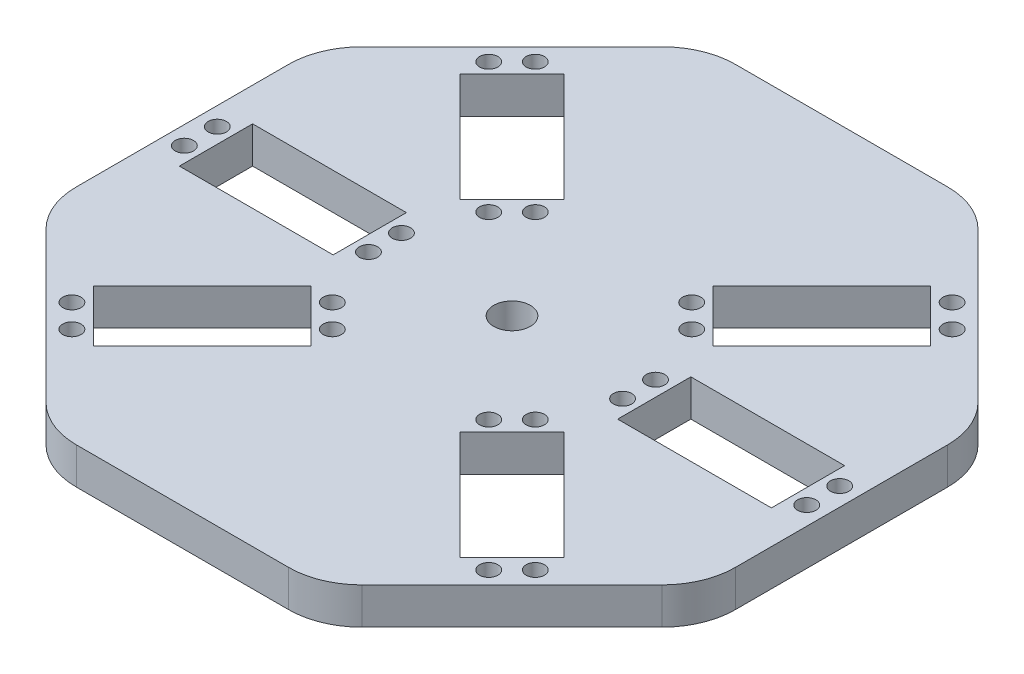
SolidWorks part; units mm, degrees
ref_plane "Front Plane" through (0, 0, 0) normal (0, 0, 1) x (1, 0, 0)
ref_plane "Top Plane" through (0, 0, 0) normal (0, 1, 0) x (1, 0, 0)
ref_plane "Right Plane" through (0, 0, 0) normal (1, 0, 0) x (0, 0, -1)
sketch "Sketch1" plane through (0, 0, 0) normal (0, 1, 0) x (1, 0, 0)
  line L0 (21.3546, -27.7186) -> (56.9221, -63.2861)
  line L1 (-90, -37.2792) -> (-37.2792, -90)
  line L2 (-37.2792, -90) -> (37.2792, -90)
  line L3 (37.2792, -90) -> (90, -37.2792)
  line L4 (90, -37.2792) -> (90, 37.2792)
  line L5 (90, 37.2792) -> (37.2792, 90)
  line L6 (37.2792, 90) -> (-37.2792, 90)
  line L7 (-37.2792, 90) -> (-90, 37.2792)
  line L8 (-90, 37.2792) -> (-90, -37.2792)
  line L9 (21.3546, -27.7186) -> (27.7186, -21.3546)
  line L10 (56.9221, -63.2861) -> (63.2861, -56.9221)
  line L11 (27.7186, -21.3546) -> (63.2861, -56.9221)
  line L12 (63.6396, -63.6396) -> (0, 0) construction
  line L13 (34.5422, -20.4) -> (20.4, -34.5422)
  line L14 (34.5422, -20.4) -> (64.2407, -50.0985)
  line L15 (20.4, -34.5422) -> (50.0985, -64.2407)
  line L16 (64.2407, -50.0985) -> (50.0985, -64.2407)
  line L17 (10, -38.85) -> (-10, -38.85) [skipped]
  line L18 (10, -38.85) -> (10, -80.85) [skipped]
  line L19 (10, -80.85) -> (-10, -80.85) [skipped]
  line L20 (-10, -38.85) -> (-10, -80.85) [skipped]
  line L21 (-20.4, -34.5422) -> (-34.5422, -20.4)
  line L22 (-20.4, -34.5422) -> (-50.0985, -64.2407)
  line L23 (-50.0985, -64.2407) -> (-64.2407, -50.0985)
  line L24 (-34.5422, -20.4) -> (-64.2407, -50.0985)
  line L25 (-38.85, -10) -> (-38.85, 10)
  line L26 (-38.85, -10) -> (-80.85, -10)
  line L27 (-80.85, -10) -> (-80.85, 10)
  line L28 (-38.85, 10) -> (-80.85, 10)
  line L29 (-34.5422, 20.4) -> (-20.4, 34.5422)
  line L30 (-34.5422, 20.4) -> (-64.2407, 50.0985)
  line L31 (-64.2407, 50.0985) -> (-50.0985, 64.2407)
  line L32 (-20.4, 34.5422) -> (-50.0985, 64.2407)
  line L33 (-10, 38.85) -> (10, 38.85) [skipped]
  line L34 (-10, 38.85) -> (-10, 80.85) [skipped]
  line L35 (-10, 80.85) -> (10, 80.85) [skipped]
  line L36 (10, 38.85) -> (10, 80.85) [skipped]
  line L37 (20.4, 34.5422) -> (34.5422, 20.4)
  line L38 (20.4, 34.5422) -> (50.0985, 64.2407)
  line L39 (50.0985, 64.2407) -> (64.2407, 50.0985)
  line L40 (34.5422, 20.4) -> (64.2407, 50.0985)
  line L41 (38.85, 10) -> (38.85, -10)
  line L42 (38.85, 10) -> (80.85, 10)
  line L43 (80.85, 10) -> (80.85, -10)
  line L44 (38.85, -10) -> (80.85, -10)
  circle A0 centre (0, 0) radius 90 construction
  circle A5 centre (56.9221, -63.2861) radius 2.5
  circle A6 centre (63.2861, -56.9221) radius 2.5
  circle A7 centre (27.7186, -21.3546) radius 2.5
  circle A8 centre (21.3546, -27.7186) radius 2.5
  circle A9 centre (-4.5, -34.7) radius 2.5 [skipped]
  circle A10 centre (4.5, -34.7) radius 2.5 [skipped]
  circle A11 centre (4.5, -85) radius 2.5 [skipped]
  circle A12 centre (-4.5, -85) radius 2.5 [skipped]
  circle A13 centre (0, 0) radius 90 construction
  circle A14 centre (-27.7186, -21.3546) radius 2.5
  circle A15 centre (-21.3546, -27.7186) radius 2.5
  circle A16 centre (-56.9221, -63.2861) radius 2.5
  circle A17 centre (-63.2861, -56.9221) radius 2.5
  circle A18 centre (0, 0) radius 90 construction
  circle A19 centre (-34.7, 4.5) radius 2.5
  circle A20 centre (-34.7, -4.5) radius 2.5
  circle A21 centre (-85, -4.5) radius 2.5
  circle A22 centre (-85, 4.5) radius 2.5
  circle A23 centre (0, 0) radius 90 construction
  circle A24 centre (-21.3546, 27.7186) radius 2.5
  circle A25 centre (-27.7186, 21.3546) radius 2.5
  circle A26 centre (-63.2861, 56.9221) radius 2.5
  circle A27 centre (-56.9221, 63.2861) radius 2.5
  circle A28 centre (0, 0) radius 90 construction
  circle A29 centre (4.5, 34.7) radius 2.5 [skipped]
  circle A30 centre (-4.5, 34.7) radius 2.5 [skipped]
  circle A31 centre (-4.5, 85) radius 2.5 [skipped]
  circle A32 centre (4.5, 85) radius 2.5 [skipped]
  circle A33 centre (0, 0) radius 90 construction
  circle A34 centre (27.7186, 21.3546) radius 2.5
  circle A35 centre (21.3546, 27.7186) radius 2.5
  circle A36 centre (56.9221, 63.2861) radius 2.5
  circle A37 centre (63.2861, 56.9221) radius 2.5
  circle A38 centre (0, 0) radius 90 construction
  circle A39 centre (34.7, -4.5) radius 2.5
  circle A40 centre (34.7, 4.5) radius 2.5
  circle A41 centre (85, 4.5) radius 2.5
  circle A42 centre (85, -4.5) radius 2.5
  circle A43 centre (0, 0) radius 90 construction
  point P15 (63.6396, -63.6396)
  point P16 (60.1041, -60.1041)
  point P17 (57.1696, -57.1696)
  point P121 (0, 0)
  dimension "D4" = 5
  dimension "D5" = 5
  dimension "D6" = 5
  dimension "D7" = 5
  dimension "D1" = 90
  dimension "D2" = 9
  dimension "D3" = 50.3
  dimension "D8" = 5
  dimension "D9" = 42
  dimension "D10" = 20
  dimension "D11" = 4.15
  dimension "D12" = 8
extrude "Boss-Extrude1" add sketch "Sketch1" along normal blind 10 contours L11 A7 L9 | L9 A7 L11 | L9 A8 L0 | L0 A8 L9 | L11 A6 L10 | L10 A6 L11 | L10 A5 L0 | L0 A5 L10 | L16 L14 L13 L11 | L16 L11 L13 L0 | L16 L0 L13 L15 | L37 L40 L39 L38 | L41 L44 L43 L42 | L29 L32 L31 L30 | L25 L28 L27 L26 | L21 L24 L23 L22 | A22 | A21 | A19 | A20 | A26 | A27 | A24 | A25 | A35 | A34 | A40 | A39 | A41 | A42 | A17 | A16 | A14 | A36 | A37 | L8 L1 L2 L3 L4 L5 L6 L7 | A15
fillet "Fillet1" radius 20 8 edges at (-90, 5, -37.2792) (-37.2792, 5, -90) (37.2792, 5, -90) (90, 5, -37.2792) (90, 5, 37.2792) (37.2792, 5, 90) (-37.2792, 5, 90) (-90, 5, 37.2792)
sketch "Sketch2" plane through (0, 10, 0) normal (0, 1, 0) x (1, 0, 0)
  circle A0 centre (0, 0) radius 5
  dimension "D1" = 10
extrude "Cut-Extrude1" cut sketch "Sketch2" against normal through all
